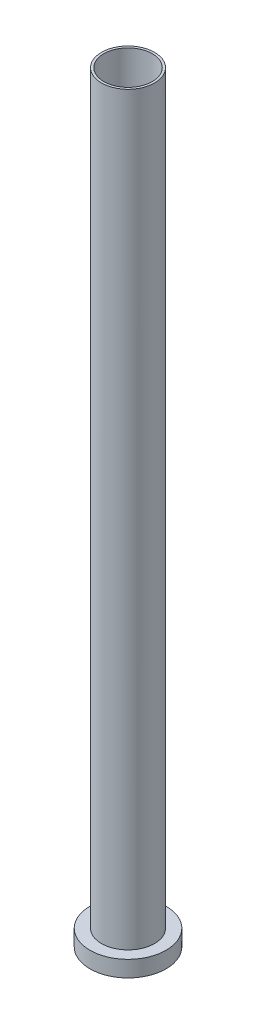
SolidWorks part; units mm, degrees
ref_plane "Front Plane" through (0, 0, 0) normal (0, 0, 1) x (1, 0, 0)
ref_plane "Top Plane" through (0, 0, 0) normal (0, 1, 0) x (1, 0, 0)
ref_plane "Right Plane" through (0, 0, 0) normal (1, 0, 0) x (0, 0, -1)
sketch "Sketch1" plane through (0, 0, 0) normal (0, 1, 0) x (1, 0, 0)
  circle A0 centre (0, 0) radius 11.5
  circle A1 centre (0, 0) radius 10.5
  dimension "D1" = 23
  dimension "D2" = 21
extrude "Boss-Extrude1" add sketch "Sketch1" along normal blind 330
sketch "Sketch2" plane through (0, 0, 0) normal (0, -1, 0) x (1, 0, 0)
  circle A0 centre (0, 0) radius 10.5
  circle A1 centre (0, 0) radius 16.5
  dimension "D1" = 33
extrude "Boss-Extrude2" add sketch "Sketch2" against normal blind 7
